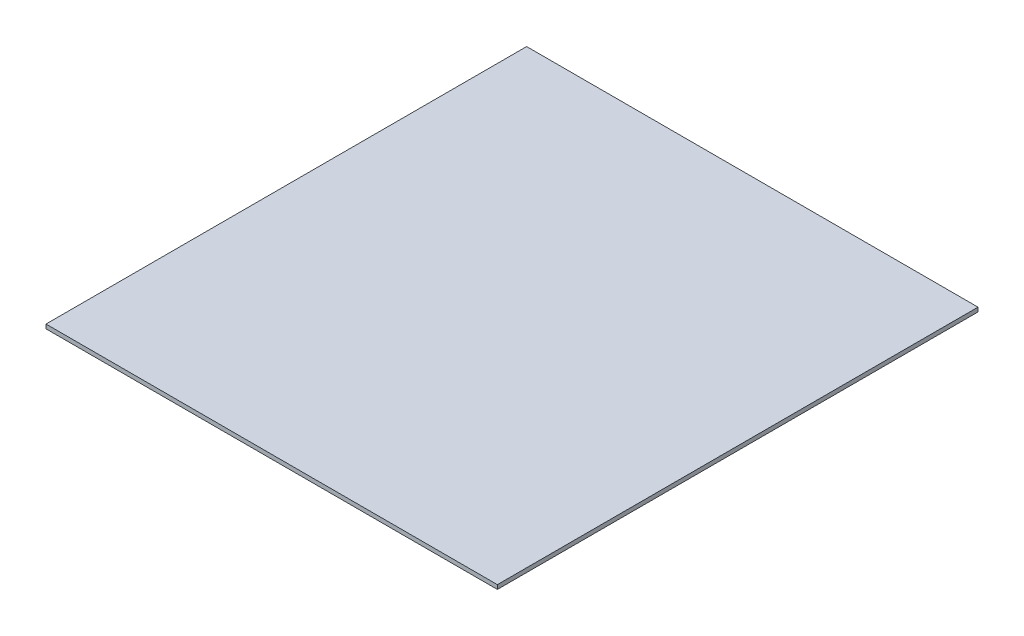
SolidWorks part; units mm, degrees
ref_plane "Front Plane" through (0, 0, 0) normal (0, 0, 1) x (1, 0, 0)
ref_plane "Top Plane" through (0, 0, 0) normal (0, 1, 0) x (1, 0, 0)
ref_plane "Right Plane" through (0, 0, 0) normal (1, 0, 0) x (0, 0, -1)
sketch "Sketch1" plane through (0, 0, 0) normal (0, 1, 0) x (1, 0, 0)
  line L1 (0, 0) -> (-540, 0)
  line L2 (0, 0) -> (0, -575)
  line L3 (0, -575) -> (-540, -575)
  line L4 (-540, 0) -> (-540, -575)
  dimension "D1" = 540
  dimension "D2" = 575
extrude "Boss-Extrude1" add sketch "Sketch1" along normal blind 5
